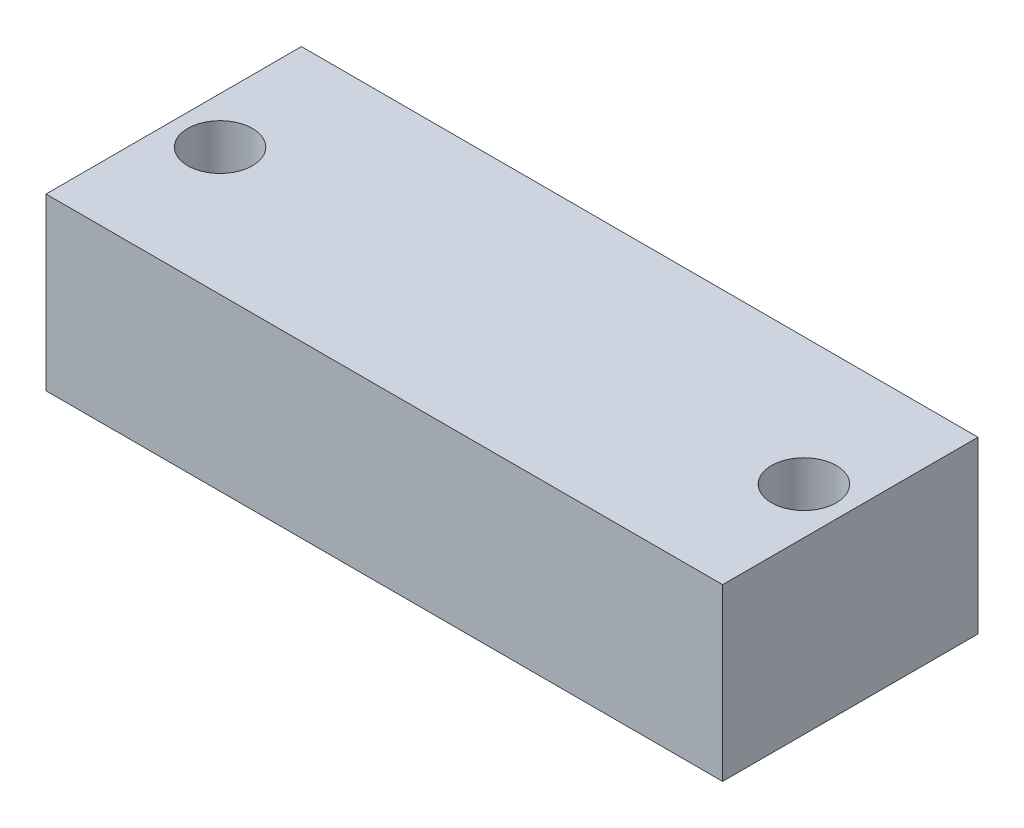
SolidWorks part; units mm, degrees
ref_plane "Front Plane" through (0, 0, 0) normal (0, 0, 1) x (1, 0, 0)
ref_plane "Top Plane" through (0, 0, 0) normal (0, 1, 0) x (1, 0, 0)
ref_plane "Right Plane" through (0, 0, 0) normal (1, 0, 0) x (0, 0, -1)
sketch "Sketch1" plane through (0, 0, 0) normal (0, 1, 0) x (1, 0, 0)
  line L1 (0, 0) -> (79.6671, 0)
  line L2 (0, 0) -> (0, 30.0736)
  line L3 (0, 30.0736) -> (79.6671, 30.0736)
  line L4 (79.6671, 0) -> (79.6671, 30.0736)
  dimension "D1" = 79.6671
  dimension "D2" = 30.0736
extrude "Boss-Extrude1" add sketch "Sketch1" along normal blind 20.066
sketch "Sketch2" plane through (0, 20.066, 0) normal (0, 1, 0) x (1, 0, 0)
  line L0 (79.6671, 0) -> (79.6671, 30.0736) construction
  line L1 (0, 30.0736) -> (0, 0) construction
  line L2 (5.461, 15.0368) -> (0, 15.0368) construction
  line L3 (74.2061, 15.0368) -> (79.6671, 15.0368) construction
  point P5 (79.6671, 15.0368)
  point P9 (0, 15.0368)
  point P13 (5.461, 15.0368)
  point P14 (74.2061, 15.0368)
  dimension "D1" = 5.461
hole_wizard "CBORE for #8 Binding Head Machine Screw2" positions "Sketch5" profile "Sketch6" counterbore size "#8" standard "ANSI Inch" end condition through all
sketch "Sketch5" plane through (0, 20.066, 0) normal (0, 1, 0) x (1, 0, 0)
  point P0 (5.461, 15.0368)
  point P3 (74.2061, 15.0368)
sketch "Sketch6" plane through (5.461, 20.066, -15.0368) normal (1, 0, 0) x (0, 0, 1)
  line L0 (0, 0) -> (0, 20.066)
  line L1 (0, 20.066) -> (2.35, 20.066)
  line L3 (2.35, 20.066) -> (2.35, 14.224)
  line L4 (2.35, 14.224) -> (3.81, 14.224)
  line L5 (3.81, 14.224) -> (3.81, 0)
  line L7 (3.81, 0) -> (0, 0)
  line L11 (0, -6.35) -> (0, 107.95) construction
  dimension "Thru Hole Dia." = 4.7
  dimension "Thru Hole Depth" = 20.066
  dimension "C'Bore Dia." = 7.62
  dimension "C'Bore Depth" = 14.224
